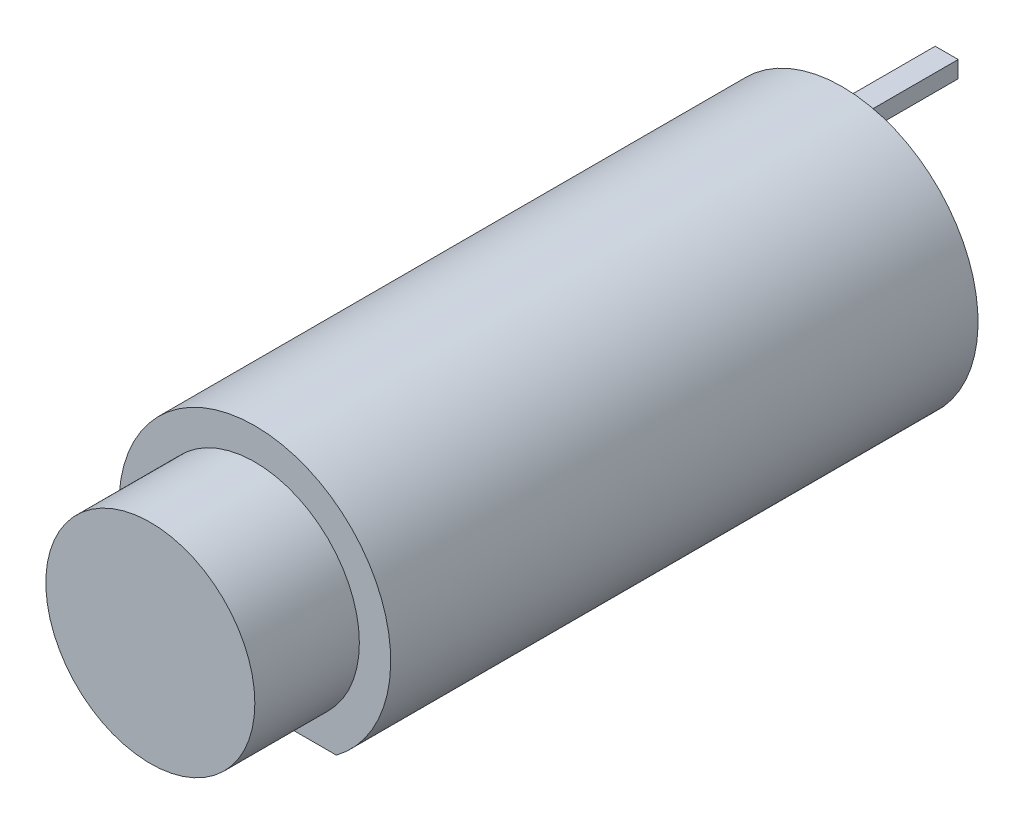
SolidWorks part; units mm, degrees
ref_plane "前视基准面" through (0, 0, 0) normal (0, 0, 1) x (1, 0, 0)
ref_plane "上视基准面" through (0, 0, 0) normal (0, 1, 0) x (1, 0, 0)
ref_plane "右视基准面" through (0, 0, 0) normal (1, 0, 0) x (0, 0, -1)
sketch "草图1" plane through (0, 0, 0) normal (0, 0, 1) x (1, 0, 0)
  line L0 (-3.9, -5.2) -> (3.9, -5.2)
  line L1 (0, -11.4382) -> (0, 5.2977) construction
  arc A0 (3.9, -5.2) -> (-3.9, -5.2) centre (0, 0) ccw
  dimension "D1" = 5.2
  dimension "D2" = 6.5
extrude "凸台-拉伸1" add sketch "草图1" along normal blind 33.1
sketch "草图2" plane through (0, 0, 33.1) normal (0, 0, 1) x (1, 0, 0)
  line L0 (-3.9, -5.2) -> (3.9, -5.2) construction
  line L1 (-3.9, -5.2) -> (3.9, -5.2)
  circle A0 centre (0, 0) radius 5
  arc A1 (3.9, -5.2) -> (-3.9, -5.2) centre (0, 0) ccw construction
  arc A2 (3.9, -5.2) -> (-3.9, -5.2) centre (0, 0) ccw
  dimension "D1" = 10
extrude "切除-拉伸1" cut sketch "草图2" against normal blind 5
sketch "草图3" plane through (0, -5.2, 0) normal (0, 0, 1) x (1, 0, 0)
  line L0 (0, -6.0259) -> (0, 38.084) construction
  line L1 (-9.2668, 10.2) -> (9.3295, 10.2) construction
  line L2 (-0.55, 10.6) -> (0.55, 10.6)
  line L3 (-0.55, 10.6) -> (-0.55, 9.8)
  line L4 (-0.55, 9.8) -> (0.55, 9.8)
  line L5 (0.55, 10.6) -> (0.55, 9.8)
  line L7 (-9.2668, 0.2) -> (9.3295, 0.2) construction
  line L8 (0.55, -0.2) -> (0.55, 0.6)
  line L9 (-0.55, 0.6) -> (0.55, 0.6)
  line L10 (-0.55, -0.2) -> (-0.55, 0.6)
  line L11 (-0.55, -0.2) -> (0.55, -0.2)
  line L12 (-16.729, 5.2) -> (22.7391, 5.2) construction
  dimension "D1" = 10
  dimension "D2" = 0.8
  dimension "D3" = 1.1
extrude "凸台-拉伸2" add sketch "草图3" against normal blind 5
